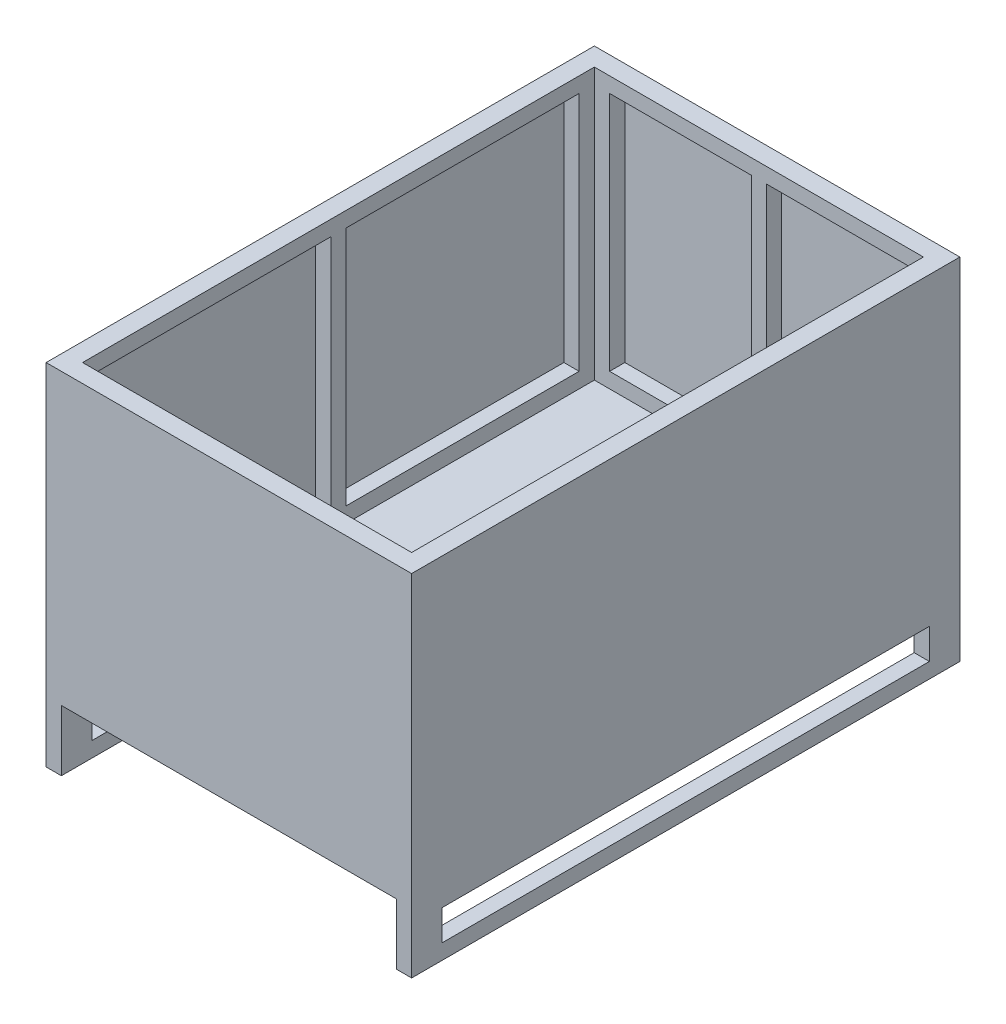
SolidWorks part; units mm, degrees
other "Markup1"
sketch "Sketch11" plane through (914.4, 457.2, -909.4) normal (0.9719, 0.2182, -0.0879) x (-0.2187, 0.7005, -0.6793)
ref_plane "Front Plane" through (0, 0, 0) normal (0, 0, 1) x (1, 0, 0)
ref_plane "Top Plane" through (0, 0, 0) normal (0, 1, 0) x (1, 0, 0)
ref_plane "Right Plane" through (0, 0, 0) normal (1, 0, 0) x (0, 0, -1)
sketch "Sketch1" plane through (0, 0, 0) normal (0, 0, 1) x (1, 0, 0)
  line L1 (0, 0) -> (609.6, 0)
  line L2 (0, 0) -> (0, 457.2)
  line L3 (0, 457.2) -> (609.6, 457.2)
  line L4 (609.6, 0) -> (609.6, 457.2)
  dimension "D1" = 609.6
  dimension "D2" = 457.2
extrude "Boss-Extrude1" add sketch "Sketch1" along normal blind 5
sketch "Sketch2" plane through (0, 0, 0) normal (0, 1, 0) x (1, 0, 0)
  line L1 (0, -5) -> (5, -5)
  line L2 (0, -5) -> (0, 909.4)
  line L3 (0, 909.4) -> (5, 909.4)
  line L4 (5, -5) -> (5, 909.4)
  dimension "D1" = 914.4
  dimension "D2" = 5
extrude "Boss-Extrude2" add sketch "Sketch2" along normal up to vertex (457.2 mm away) up to point (0, 457.2, 0)
ref_plane "Plane1" through (0, 0, -909.4) normal (0, 0, -1) x (-1, 0, 0)
sketch "Sketch3" plane through (0, 0, -909.4) normal (0, 0, -1) x (-1, 0, 0)
  line L0 (-609.6, 0) -> (-609.6, 457.2) construction
  line L1 (0, 457.2) -> (-609.6, 457.2)
  line L2 (0, 457.2) -> (0, 0)
  line L3 (0, 0) -> (-609.6, 0)
  line L4 (-609.6, 457.2) -> (-609.6, 0)
extrude "Boss-Extrude3" add sketch "Sketch3" against normal blind 5
ref_plane "Plane2" through (609.6, 0, 0) normal (1, 0, 0) x (0, 0, -1)
sketch "Sketch4" plane through (609.6, 0, 0) normal (1, 0, 0) x (0, 0, -1)
  line L1 (-5, 457.2) -> (909.4, 457.2)
  line L2 (-5, 457.2) -> (-5, 0)
  line L3 (-5, 0) -> (909.4, 0)
  line L4 (909.4, 457.2) -> (909.4, 0)
extrude "Boss-Extrude4" add sketch "Sketch4" against normal blind 5
sketch "Sketch5" plane through (0, 0, 0) normal (0, -1, 0) x (-1, 0, 0)
  line L2 (-609.6, -5) -> (-609.6, 909.4)
  line L3 (-609.6, 909.4) -> (0, 909.4)
  line L4 (0, -5) -> (0, 909.4)
  line L7 (-609.6, -5) -> (-609.6, 909.4) construction
  line L8 (0, -5) -> (-609.6, -5)
extrude "Boss-Extrude5" add sketch "Sketch5" against normal blind 5
sketch "Sketch6" plane through (0, 0, 0) normal (0, -1, 0) x (1, 0, 0)
  line L5 (609.6, -909.4) -> (0, -909.4) construction
  line L13 (25.4, -20.4) -> (584.2, -20.4)
  line L15 (0, 5) -> (609.6, 5) construction
  line L19 (25.4, -20.4) -> (25.4, -884)
  line L22 (25.4, -884) -> (584.2, -884)
  line L27 (584.2, -20.4) -> (584.2, -884)
  line L28 (609.6, 5) -> (609.6, -909.4) construction
  line L29 (0, 5) -> (0, -909.4) construction
  line L32 (609.6, -909.4) -> (609.6, 5)
  line L34 (0, -909.4) -> (609.6, -909.4)
  line L35 (609.6, -909.4) -> (609.6, 5)
  line L36 (609.6, 5) -> (0, 5)
  line L37 (0, 5) -> (0, -909.4)
  line L38 (0, -909.4) -> (609.6, -909.4)
  line L40 (609.6, 5) -> (0, 5)
  line L41 (0, 5) -> (0, -909.4)
  dimension "D1" = 25.4
  dimension "D2" = 25.4
  dimension "D3" = 25.4
  dimension "D4" = 25.4
  dimension "D5" = 0
extrude "Boss-Extrude6" add sketch "Sketch6" along normal blind 25.4 contours L40 L41 L38 L35
sketch "Sketch7" plane through (0, 0, 0) normal (0, -1, 0) x (1, 0, 0)
  line L0 (584.2, -20.4) -> (25.4, -20.4) construction
  line L1 (292.1, -20.4) -> (317.5, -20.4)
  line L2 (292.1, -20.4) -> (292.1, -884)
  line L3 (292.1, -884) -> (317.5, -884)
  line L4 (317.5, -20.4) -> (317.5, -884)
  line L5 (609.6, 5) -> (0, 5) construction
  line L6 (25.4, -884) -> (584.2, -884) construction
  point P8 (304.8, 5)
  point P9 (304.8, -20.4)
  dimension "D1" = 25.4
extrude "Boss-Extrude7" add sketch "Sketch7" along normal blind 25.4
ref_plane "Plane3" through (304.8, 457.2, -904.4) normal (1, 0, 0) x (0, 0, -1)
sketch "Sketch10" plane through (604.6, 0, 0) normal (-1, 0, 0) x (0, 0, 1)
  line L0 (-25.4, 431.8) -> (-879, 431.8)
  line L1 (-879, 431.8) -> (-879, 30.4)
  line L2 (-879, 30.4) -> (-25.4, 30.4)
  line L3 (-25.4, 30.4) -> (-25.4, 431.8)
  line L4 (-904.4, 457.2) -> (-904.4, 5)
  line L5 (-904.4, 5) -> (0, 5)
  line L6 (0, 5) -> (0, 457.2)
  line L7 (0, 457.2) -> (-904.4, 457.2)
  line L8 (-904.4, 457.2) -> (-904.4, 5)
  line L9 (-904.4, 5) -> (0, 5)
  line L10 (0, 5) -> (0, 457.2)
  line L11 (0, 457.2) -> (-904.4, 457.2)
  dimension "D1" = 0
  dimension "D2" = 25.4
extrude "Boss-Extrude8" add sketch "Sketch10" along normal blind 25.4
mirror "Mirror3" about plane through (304.8, 457.2, -904.4) normal (1, 0, 0) of bodies 108
ref_plane "Plane4" through (0, 0, -452.2) normal (0, 0, 1) x (1, 0, 0)
sketch "Sketch15" plane through (5, 0, 0) normal (1, 0, 0) x (0, 0, -1)
  line L0 (879, 30.4) -> (25.4, 30.4) construction
  line L1 (25.4, 431.8) -> (50.8, 431.8)
  line L2 (25.4, 431.8) -> (25.4, 30.4)
  line L3 (25.4, 30.4) -> (50.8, 30.4)
  line L4 (50.8, 431.8) -> (50.8, 30.4)
  line L5 (25.4, 431.8) -> (879, 431.8) construction
  line L6 (879, 431.8) -> (853.6, 431.8)
  line L7 (879, 431.8) -> (879, 30.4)
  line L8 (879, 30.4) -> (853.6, 30.4)
  line L9 (853.6, 431.8) -> (853.6, 30.4)
  line L10 (439.5, 431.8) -> (464.9, 431.8)
  line L11 (439.5, 431.8) -> (439.5, 30.4)
  line L13 (464.9, 431.8) -> (464.9, 30.4)
  line L14 (0, 457.2) -> (904.4, 457.2) construction
  line L17 (439.5, 30.4) -> (464.9, 30.4)
  point P20 (452.2, 457.2)
  point P21 (452.2, 431.8)
  dimension "D1" = 25.4
  dimension "D2" = 25.4
  dimension "D3" = 25.4
sketch "Sketch17" plane through (0, 0, 5) normal (1, 0, 0) x (0, 0, -1)
  line L9 (0, -25.4) -> (0, -127)
  line L12 (0, -127) -> (914.4, -127)
  line L13 (914.4, -127) -> (914.4, -25.4)
  line L15 (914.4, -25.4) -> (0, -25.4) construction
  line L16 (50.8, -50.8) -> (863.6, -50.8)
  line L17 (50.8, -50.8) -> (50.8, -101.6)
  line L18 (50.8, -101.6) -> (863.6, -101.6)
  line L19 (863.6, -50.8) -> (863.6, -101.6)
  line L20 (914.4, -25.4) -> (0, -25.4)
  dimension "D1" = 101.6
  dimension "D2" = 25.4
  dimension "D3" = 25.4
  dimension "D4" = 50.8
  dimension "D5" = 50.8
sketch "Sketch19" plane through (0, -25.4, 0) normal (0, -1, 0) x (1, 0, 0)
  line L0 (609.6, -452.2) -> (0, -452.2)
  line L3 (609.6, -884) -> (609.6, -20.4) construction
  line L4 (0, -20.4) -> (0, -884) construction
sketch "Sketch22" plane through (0, 0, -904.4) normal (0, 0, 1) x (1, 0, 0)
  line L0 (55.8, 431.8) -> (292.1, 431.8)
  line L1 (30.4, 457.2) -> (579.2, 457.2)
  line L2 (30.4, 457.2) -> (30.4, 5)
  line L3 (30.4, 5) -> (579.2, 5)
  line L4 (579.2, 457.2) -> (579.2, 5)
  line L5 (553.8, 431.8) -> (553.8, 30.4)
  line L6 (55.8, 30.4) -> (292.1, 30.4)
  line L7 (55.8, 431.8) -> (55.8, 30.4)
  line L8 (304.8, 431.8) -> (304.8, 30.4) construction
  line L9 (317.5, 431.8) -> (317.5, 30.4)
  line L10 (292.1, 431.8) -> (292.1, 30.4)
  line L11 (317.5, 431.8) -> (553.8, 431.8)
  line L12 (55.8, 431.8) -> (553.8, 431.8) construction
  line L13 (317.5, 30.4) -> (553.8, 30.4)
  line L14 (55.8, 30.4) -> (553.8, 30.4) construction
  point P17 (304.8, 457.2)
  dimension "D1" = 25.4
  dimension "D2" = 12.7
extrude "Boss-Extrude14" add sketch "Sketch22" along normal blind 25.4 contours L0 L10 L6 L7
extrude "Boss-Extrude15" add sketch "Sketch15" along normal blind 25.4
sketch "Sketch23" plane through (604.6, 0, 0) normal (-1, 0, 0) x (0, 0, 1)
  line L0 (-879, 431.8) -> (-853.6, 431.8)
  line L1 (-25.4, 431.8) -> (-879, 431.8) construction
  line L2 (-853.6, 431.8) -> (-853.6, 30.4)
  line L3 (-879, 30.4) -> (-25.4, 30.4) construction
  line L4 (-853.6, 30.4) -> (-879, 30.4)
  line L5 (-879, 30.4) -> (-879, 431.8)
  line L6 (-25.4, 431.8) -> (-879, 431.8) construction
  line L7 (-25.4, 431.8) -> (-50.8, 431.8)
  line L8 (-25.4, 431.8) -> (-25.4, 30.4)
  line L9 (-25.4, 30.4) -> (-50.8, 30.4)
  line L10 (-50.8, 431.8) -> (-50.8, 30.4)
  line L11 (-464.9, 431.8) -> (-439.5, 431.8)
  line L12 (-464.9, 431.8) -> (-464.9, 30.4)
  line L13 (-464.9, 30.4) -> (-439.5, 30.4)
  line L14 (-439.5, 431.8) -> (-439.5, 30.4)
  line L15 (-879, 30.4) -> (-25.4, 30.4) construction
  line L16 (-879, 30.4) -> (-25.4, 30.4)
  point P23 (-452.2, 30.4)
  point P24 (-452.2, 30.4)
  line M13 (-879, 30.4) -> (-25.4, 30.4)
  line M14 (-25.4, 30.4) -> (-25.4, 431.8)
  line M15 (-25.4, 431.8) -> (-879, 431.8)
  dimension "D1" = 25.4
  dimension "D2" = 25.4
  dimension "D3" = 25.4
extrude "Boss-Extrude16" add sketch "Sketch23" along normal blind 25.4 contours L10 M15 M13 M14 | L12 L13 L14 L11 | L5 L0 L2 L4
mirror "Mirror9" about plane through (0, 0, -452.2) normal (0, 0, 1) of bodies 121
extrude "Boss-Extrude17" add sketch "Sketch17" along normal blind 25.4
mirror "Mirror10" about plane through (304.8, 457.2, -904.4) normal (1, 0, 0) of bodies 124
sketch "Sketch25" plane through (0, -25.4, 0) normal (0, -1, 0) x (1, 0, 0)
  line L0 (292.1, -20.4) -> (317.5, -20.4)
  line L1 (317.5, -20.4) -> (317.5, -884)
  line L2 (317.5, -884) -> (292.1, -884)
  line L3 (292.1, -884) -> (292.1, -20.4)
extrude "Cut-Extrude1" cut sketch "Sketch25" against normal blind 25.4
sketch "Sketch26" plane through (0, 0, 0) normal (0, -1, 0) x (1, 0, 0)
  line L0 (25.4, -884) -> (25.4, -20.4) construction
  line L1 (25.4, -464.9) -> (584.2, -464.9)
  line L2 (25.4, -464.9) -> (25.4, -439.5)
  line L3 (25.4, -439.5) -> (584.2, -439.5)
  line L4 (584.2, -464.9) -> (584.2, -439.5)
  line L5 (584.2, -20.4) -> (584.2, -884) construction
  point P8 (25.4, -452.2)
  point P9 (25.4, -452.2)
  dimension "D1" = 25.4
extrude "Boss-Extrude18" add sketch "Sketch26" along normal blind 25.4
ref_plane "Plane5" through (0, 0, -452.2) normal (0, 0, 1) x (1, 0, 0)
